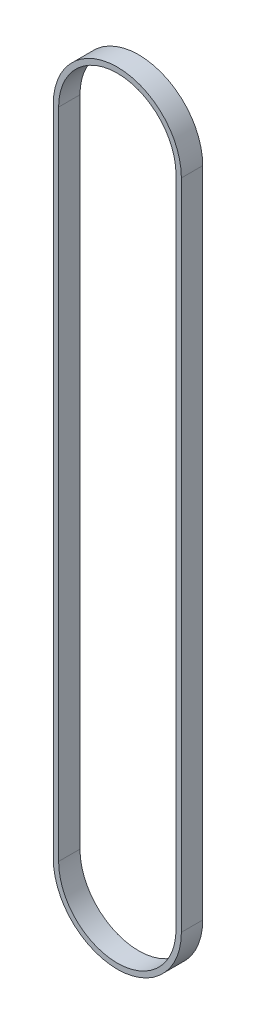
SolidWorks part; units mm, degrees
material "Natural Rubber"
ref_plane "Front Plane" through (0, 0, 0) normal (0, 0, 1) x (1, 0, 0)
ref_plane "Top Plane" through (0, 0, 0) normal (0, 1, 0) x (1, 0, 0)
ref_plane "Right Plane" through (0, 0, 0) normal (1, 0, 0) x (0, 0, -1)
sketch "Sketch1" plane through (0, 0, 0) normal (0, 0, 1) x (1, 0, 0)
  line L0 (0, -55) -> (0, 55) construction
  line L1 (-76.2, -366.4893) -> (-76.2, 410.7507)
  line L2 (-69.85, 410.7507) -> (-69.85, -366.4893)
  line L3 (69.85, -366.4893) -> (69.85, 410.7507)
  line L5 (76.2, -366.4893) -> (76.2, 410.7507)
  arc A0 (69.85, 410.7507) -> (-69.85, 410.7507) centre (0, 410.7507) ccw
  arc A1 (76.2, 410.7507) -> (-76.2, 410.7507) centre (0, 410.7507) ccw
  arc A2 (69.85, -366.4893) -> (-69.85, -366.4893) centre (0, -366.4893) cw
  arc A3 (-76.2, -366.4893) -> (76.2, -366.4893) centre (0, -366.4893) ccw
  dimension "D1" = 76.2
  dimension "D2" = 69.85
  dimension "D3" = 777.24
extrude "Boss-Extrude1" add sketch "Sketch1" along normal blind 25.4
